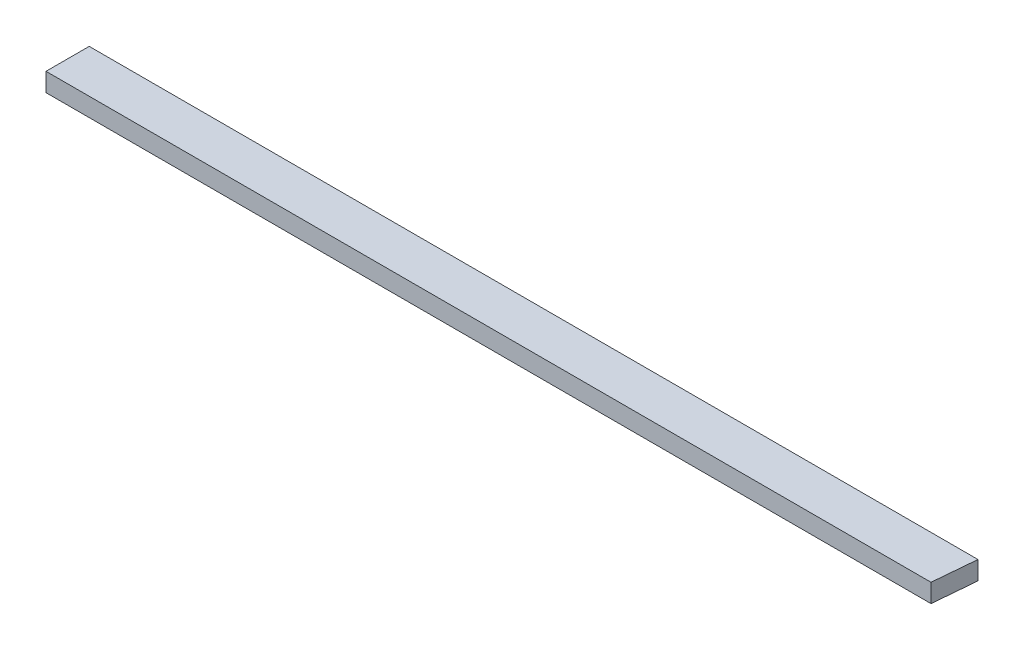
SolidWorks part; units mm, degrees
ref_plane "Front Plane" through (0, 0, 0) normal (0, 0, 1) x (1, 0, 0)
ref_plane "Top Plane" through (0, 0, 0) normal (0, 1, 0) x (1, 0, 0)
ref_plane "Right Plane" through (0, 0, 0) normal (1, 0, 0) x (0, 0, -1)
sketch "Sketch1" plane through (0, 0, 0) normal (0, 1, 0) x (1, 0, 0)
  line L0 (1828.8, 88.9) -> (1821.0223, 0)
  line L1 (0, 0) -> (1821.0223, 0)
  line L2 (0, 0) -> (0, 88.9)
  line L3 (0, 88.9) -> (1828.8, 88.9)
  line L5 (1670.307, 88.9) -> (1670.307, 0) construction
  line L6 (1573.2898, 88.9) -> (1573.2898, 0) construction
  line L7 (1476.2726, 88.9) -> (1476.2726, 0) construction
  line L8 (1379.2554, 88.9) -> (1379.2554, 0) construction
  line L9 (1282.2381, 88.9) -> (1282.2381, 0) construction
  line L10 (1185.2209, 88.9) -> (1185.2209, 0) construction
  line L11 (1088.2037, 88.9) -> (1088.2037, 0) construction
  line L12 (991.1864, 88.9) -> (991.1864, 0) construction
  line L13 (894.1692, 88.9) -> (894.1692, 0) construction
  line L14 (797.152, 88.9) -> (797.152, 0) construction
  line L15 (700.1347, 88.9) -> (700.1347, 0) construction
  line L16 (603.1175, 88.9) -> (603.1175, 0) construction
  line L17 (506.1003, 88.9) -> (506.1003, 0) construction
  line L18 (409.0831, 88.9) -> (409.0831, 0) construction
  line L19 (312.0658, 88.9) -> (312.0658, 0) construction
  line L20 (215.0486, 88.9) -> (215.0486, 0) construction
  line L22 (118.0314, 88.9) -> (118.0314, 0) [skipped]
  dimension "D1" = 88.9
  dimension "D2" = 1828.8
  dimension "D3" = 85
  dimension "D4" = 17
  dimension "D5" = 158.493
  dimension "D6" = 255.5102
  dimension "D7" = 352.5274
  dimension "D8" = 449.5446
  dimension "D9" = 546.5619
  dimension "D10" = 643.5791
  dimension "D11" = 740.5963
  dimension "D12" = 837.6136
  dimension "D13" = 934.6308
  dimension "D14" = 97.0172
  dimension "D15" = 1031.648
  dimension "D16" = 1128.6653
  dimension "D17" = 1225.6825
  dimension "D18" = 1322.6997
  dimension "D20" = 1613.7514
extrude "Boss-Extrude1" add sketch "Sketch1" against normal blind 38.1
